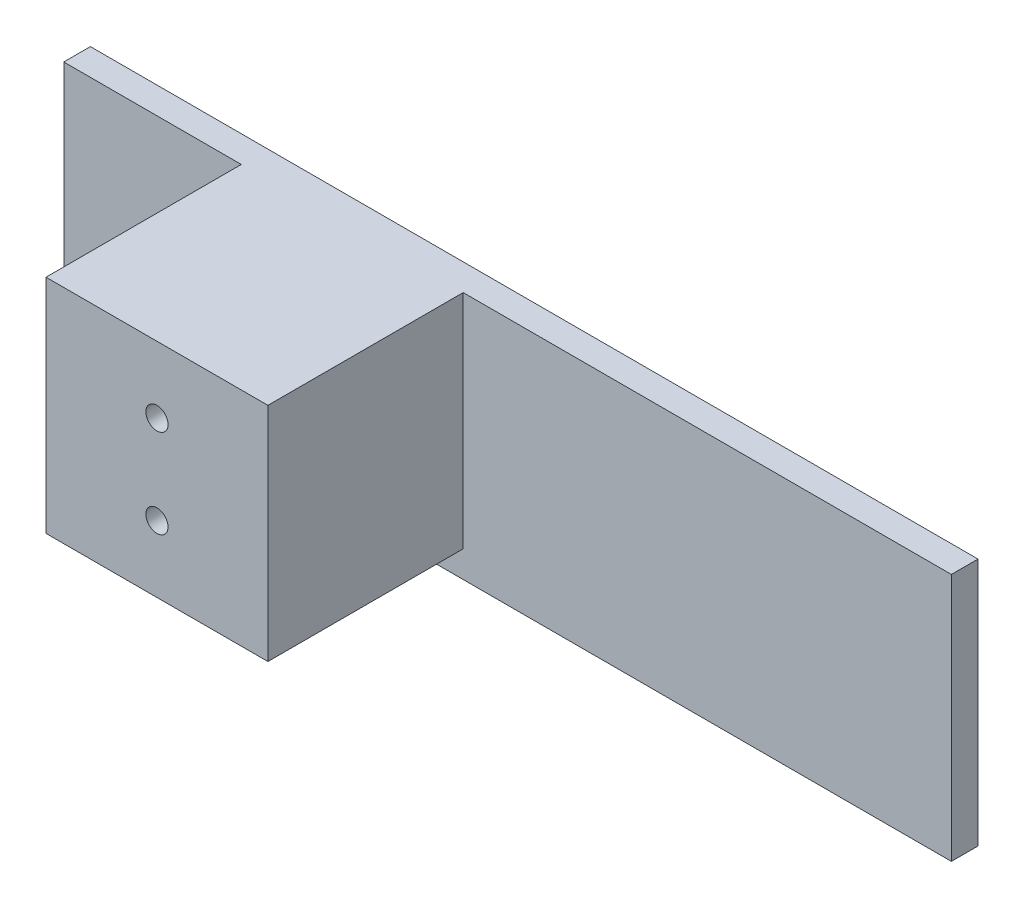
SolidWorks part; units mm, degrees
ref_plane "Plan de face" through (0, 0, 0) normal (0, 0, 1) x (1, 0, 0)
ref_plane "Plan de dessus" through (0, 0, 0) normal (0, 1, 0) x (1, 0, 0)
ref_plane "Plan de droite" through (0, 0, 0) normal (1, 0, 0) x (0, 0, -1)
sketch "Esquisse1" plane through (0, 0, 0) normal (0, 0, 1) x (1, 0, 0)
  line L1 (-17.2348, 13.2576) -> (7.7652, 13.2576)
  line L2 (-17.2348, 13.2576) -> (-17.2348, -11.7424)
  line L3 (-17.2348, -11.7424) -> (7.7652, -11.7424)
  line L4 (7.7652, 13.2576) -> (7.7652, -11.7424)
  dimension "D1" = 25
  dimension "D2" = 25
extrude "Boss.-Extru.1" add sketch "Esquisse1" along normal blind 22
sketch "Esquisse2" plane through (0, 0, 22) normal (0, 0, 1) x (1, 0, 0)
  line L0 (-17.2348, 0.7576) -> (7.7652, 0.7576) construction
  line L1 (-17.2348, 13.2576) -> (-17.2348, -11.7424) construction
  line L2 (7.7652, -11.7424) -> (7.7652, 13.2576) construction
  line L3 (-4.7348, 5.7576) -> (-4.7348, -4.2424) construction
  circle A0 centre (-4.7348, 5.7576) radius 1.25
  circle A1 centre (-4.7348, -4.2424) radius 1.25
  point P13 (-4.7348, 0.7576)
  point P14 (-4.7348, 0.7576)
  dimension "D2" = 2.5
  dimension "D1" = 10
extrude "Enlèv. mat.-Extru.1" cut sketch "Esquisse2" against normal blind 15
sketch "Esquisse3" plane through (0, 0, 0) normal (0, 0, -1) x (-1, 0, 0)
  line L0 (-7.7652, 13.2576) -> (17.2348, 13.2576) construction
  line L1 (37.2348, -14.7424) -> (-62.7652, -14.7424)
  line L2 (37.2348, -14.7424) -> (37.2348, 13.2576)
  line L3 (37.2348, 13.2576) -> (-62.7652, 13.2576)
  line L4 (-62.7652, -14.7424) -> (-62.7652, 13.2576)
  line L7 (17.2348, -11.7424) -> (-7.7652, -11.7424) construction
  line L8 (17.2348, 13.2576) -> (17.2348, -11.7424) construction
  line L9 (-7.7652, -11.7424) -> (-7.7652, 13.2576) construction
  dimension "D1" = 3
  dimension "D2" = 20
  dimension "D3" = 55
extrude "Boss.-Extru.2" add sketch "Esquisse3" along normal blind 3
